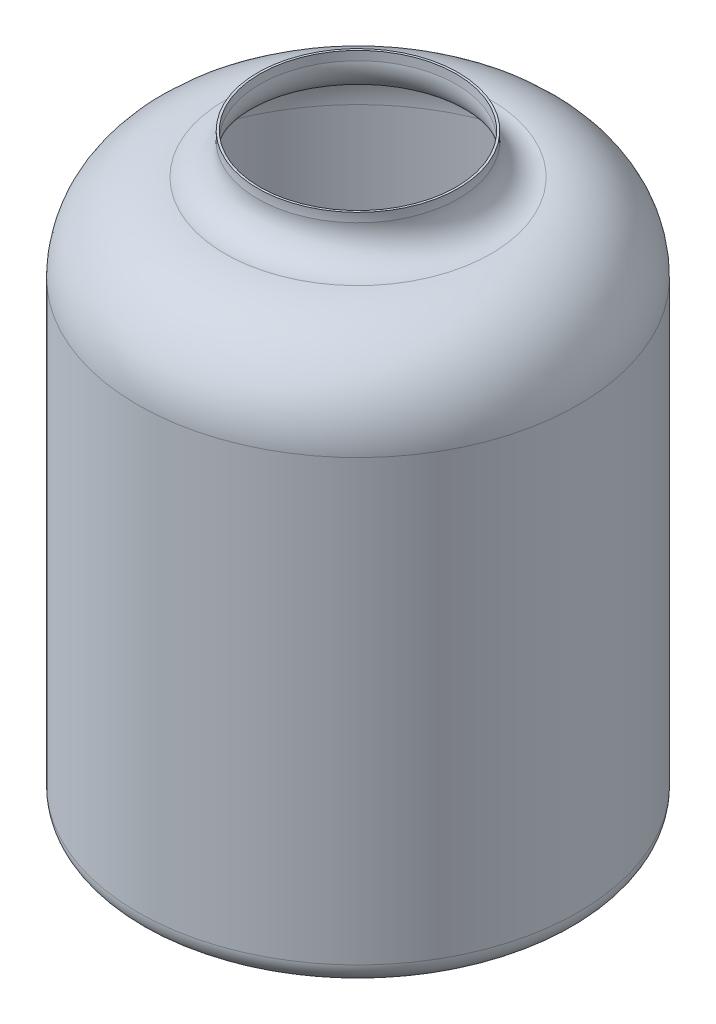
SolidWorks part; units mm, degrees
material "Acrylic (Medium-high impact)"
ref_plane "Front Plane" through (0, 0, 0) normal (0, 0, 1) x (1, 0, 0)
ref_plane "Top Plane" through (0, 0, 0) normal (0, 1, 0) x (1, 0, 0)
ref_plane "Right Plane" through (0, 0, 0) normal (1, 0, 0) x (0, 0, -1)
sketch "Sketch2" plane through (0, 0, 0) normal (0, 0, 1) x (1, 0, 0)
  line L0 (0, 1) -> (0, 40) construction
  line L19 (85.4619, 0) -> (0, 0)
  line L30 (85.4619, 1) -> (1, 1)
  line L32 (0, 253.7094) -> (0, 0) construction
  line L33 (1, 252.7094) -> (1, 1) construction
  line L34 (1, 1) -> (0, 1)
  line L35 (0, 1) -> (0, 0)
  line L42 (20, 253.7094) -> (0, 253.7094) construction
  line L43 (20, 252.7094) -> (1, 252.7094) construction
  line L44 (46, 270) -> (46, 265.8654)
  line L45 (40, 227.1459) -> (40, 233.7094) construction
  line L46 (39, 227.1459) -> (39, 233.7094) construction
  line L50 (64, 216.1197) -> (42.1276, 216.1197) construction
  line L51 (63.8126, 217.1197) -> (42.6947, 217.1197) construction
  line L53 (100, 190.2508) -> (100, 36.0475) construction
  line L54 (101, 190.2264) -> (101, 37.6248) construction
  line L59 (46, 270) -> (45, 270)
  line L60 (85.4619, 1) -> (90, 1)
  line L61 (102.4181, 12.8141) -> (92.5329, 2.9289) construction
  line L62 (102.1318, 13.942) -> (91.8258, 3.636) construction
  line L63 (100, 11) -> (100, 36.0475)
  line L64 (85.4619, 0) -> (91, 0)
  line L65 (101, 10) -> (101, 37.6248)
  line L72 (100, 209.5941) -> (100, 36.0475)
  line L73 (101, 37.6248) -> (101, 211.5012)
  line L76 (57.936, 249.5941) -> (60, 249.5941)
  line L77 (45, 270) -> (45, 265.8654)
  arc A16 (20, 253.7094) -> (40, 233.7094) centre (20, 233.7094) cw construction
  arc A17 (20, 252.7094) -> (39, 233.7094) centre (20, 233.7094) cw construction
  arc A18 (42.6947, 217.1197) -> (40, 227.1459) centre (60, 227.1459) cw construction
  arc A19 (42.1276, 216.1197) -> (39, 227.1459) centre (60, 227.1459) cw construction
  arc A20 (101, 190.2264) -> (63.8126, 217.1197) centre (73.6417, 191.5536) ccw construction
  arc A21 (100, 190.2508) -> (64, 216.1197) centre (73.6417, 191.5536) ccw construction
  arc A22 (100, 36.0475) -> (102.1318, 13.942) centre (105.8499, 25.4561) cw construction
  arc A23 (101, 37.6248) -> (102.4181, 12.8141) centre (105.8499, 25.4561) cw construction
  arc A24 (91.8258, 3.636) -> (85.4619, 1) centre (85.4619, 10) cw construction
  arc A25 (92.5329, 2.9289) -> (85.4619, 0) centre (85.4619, 10) cw construction
  arc A26 (91, 0) -> (101, 10) centre (91, 10) ccw
  arc A27 (90, 1) -> (100, 11) centre (90, 11) ccw
  arc A32 (101, 211.5012) -> (61, 251.5012) centre (61, 211.5012) ccw
  arc A33 (60, 249.5941) -> (100, 209.5941) centre (60, 209.5941) cw
  arc A34 (46, 265.8654) -> (61, 251.5012) centre (59.7103, 265.1685) ccw
  arc A35 (45, 265.8654) -> (57.936, 249.5941) centre (59.6036, 264.1977) ccw
  arc A36 (57.936, 249.5941) -> (60, 249.5941) centre (58.968, 263.6924) ccw
  spline S0 degree 2 poles (46, 270) (45.8437, 267.8047) (46, 265.8654) knots 0 0 0 0.134328 0.134328 0.134328
  point P15 (40, 253.7094)
  point P20 (100, 216.6103)
  dimension "D4" = 10
  dimension "D5" = 100
  dimension "D3" = 40
  dimension "D7" = 60.4059
  dimension "D8" = 58.4988
  dimension "D9" = 270
  dimension "D6" = 1
revolve "Revolve1" add sketch "Sketch2" angle 360 about L0
